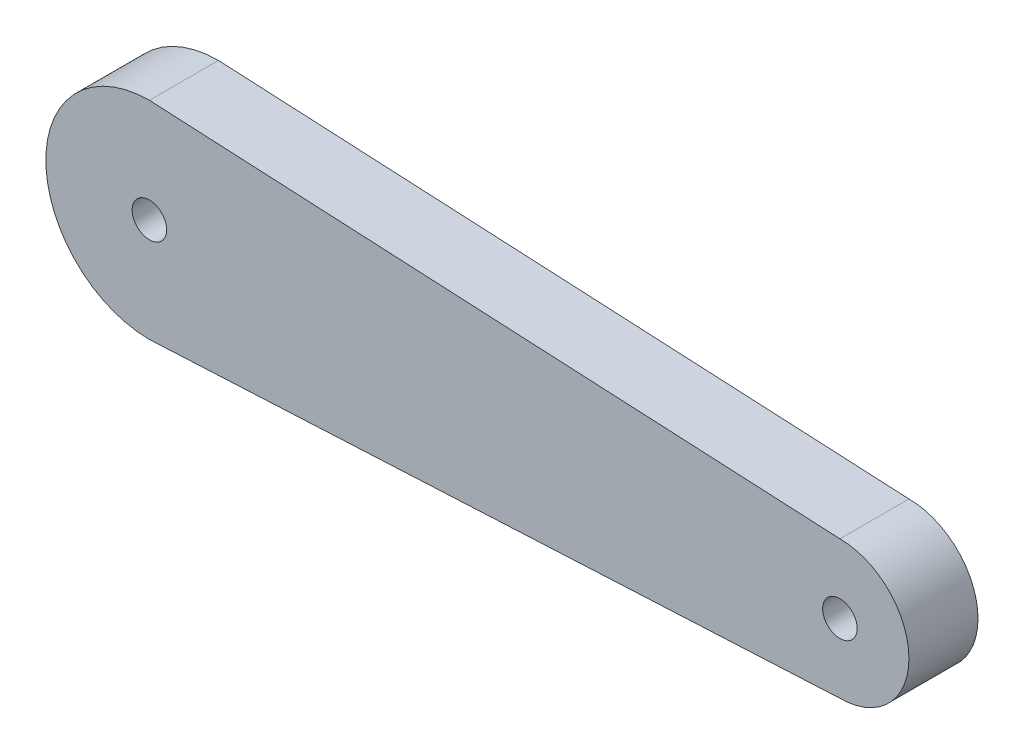
SolidWorks part; units mm, degrees
ref_plane "Front Plane" through (0, 0, 0) normal (0, 0, 1) x (1, 0, 0)
ref_plane "Top Plane" through (0, 0, 0) normal (0, 1, 0) x (1, 0, 0)
ref_plane "Right Plane" through (0, 0, 0) normal (1, 0, 0) x (0, 0, -1)
sketch "Sketch1" plane through (0, 0, 0) normal (0, 0, 1) x (1, 0, 0)
  line L1 (-37.8454, 14.1818) -> (62.1546, 9.1818)
  line L3 (-37.8454, -15.8182) -> (62.1546, -10.8182)
  circle A0 centre (62.1546, -0.8182) radius 10
  circle A1 centre (-37.8454, -0.8182) radius 15
  dimension "D5" = 20
  dimension "D7" = 30
  dimension "D1" = 20
  dimension "D2" = 30
  dimension "D4" = 100
extrude "Boss-Extrude1" add sketch "Sketch1" along normal blind 10 contours L1 A1 L3 | A1 L3 A0 L1 | A0
sketch "Sketch9" plane through (0, 0, 10) normal (0, 0, 1) x (1, 0, 0)
  circle A0 centre (-37.8454, -0.8182) radius 2.5
  circle A1 centre (62.1546, -0.8182) radius 2.5
  arc A2 (-37.8454, 14.1818) -> (-37.8454, -15.8182) centre (-37.8454, -0.8182) ccw construction
  arc A3 (62.1546, -10.8182) -> (62.1546, 9.1818) centre (62.1546, -0.8182) ccw construction
  dimension "D1" = 5
  dimension "D2" = 5
  dimension "D4" = 0
  dimension "D3" = 0
extrude "Cut-Extrude7" cut sketch "Sketch9" against normal blind 10
